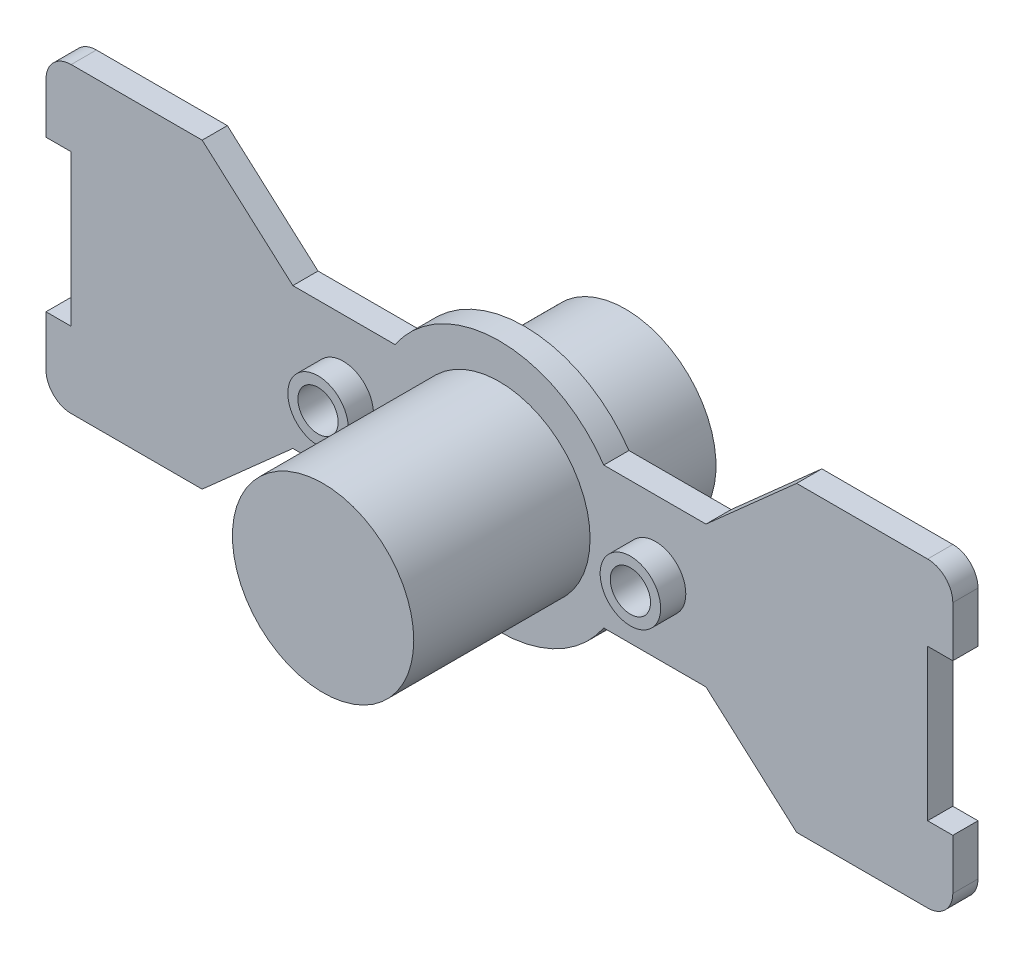
SolidWorks part; units mm, degrees
ref_plane "前视基准面" through (0, 0, 0) normal (0, 0, 1) x (1, 0, 0)
ref_plane "上视基准面" through (0, 0, 0) normal (0, 1, 0) x (1, 0, 0)
ref_plane "右视基准面" through (0, 0, 0) normal (1, 0, 0) x (0, 0, -1)
sketch "草图1" plane through (0, 0, 0) normal (0, 0, 1) x (1, 0, 0)
  line L0 (-20.7123, 14) -> (-41, 14)
  line L1 (-41, 14) -> (-59, 30)
  line L2 (-59, 30) -> (-90, 30)
  line L3 (-90, 15) -> (-90, 30)
  line L4 (-90, 15) -> (-85, 15)
  line L5 (-85, 15) -> (-85, -15)
  line L6 (-85, -15) -> (-90, -15)
  line L7 (-90, -15) -> (-90, -30)
  line L8 (-90, -30) -> (-59, -30)
  line L9 (-59, -30) -> (-41, -14)
  line L10 (-41, -14) -> (-20.7123, -14)
  line L12 (0, 25) -> (0, 38.7595) construction
  line L13 (41, -14) -> (20.7123, -14)
  line L14 (59, -30) -> (41, -14)
  line L15 (90, -30) -> (59, -30)
  line L16 (90, -15) -> (90, -30)
  line L17 (85, -15) -> (90, -15)
  line L18 (85, 15) -> (85, -15)
  line L19 (90, 15) -> (85, 15)
  line L20 (90, 15) -> (90, 30)
  line L21 (59, 30) -> (90, 30)
  line L22 (20.7123, 14) -> (41, 14)
  line L23 (41, 14) -> (59, 30)
  line L24 (25, 0) -> (85, 0) construction
  arc A0 (20.7123, 14) -> (-20.7123, 14) centre (0, 0) ccw
  arc A1 (-20.7123, -14) -> (20.7123, -14) centre (0, 0) ccw
  point P17 (0, 0)
  dimension "D1" = 50
  dimension "D2" = 41
  dimension "D3" = 59
  dimension "D4" = 85
  dimension "D5" = 90
  dimension "D6" = 30
  dimension "D7" = 60
  dimension "D8" = 28
extrude "凸台-拉伸1" add sketch "草图1" along normal blind 5
sketch "草图2" plane through (0, 0, 5) normal (0, 0, 1) x (1, 0, 0)
  circle A0 centre (0, 0) radius 18
extrude "凸台-拉伸2" add sketch "草图2" along normal blind 35
sketch "草图3" plane through (0, 0, 0) normal (0, 0, -1) x (-1, 0, 0)
  circle A0 centre (0, 0) radius 18
extrude "凸台-拉伸3" add sketch "草图3" along normal blind 20
sketch "草图4" plane through (0, 0, -20) normal (0, 0, -1) x (-1, 0, 0)
  circle A0 centre (0, 0) radius 15
  dimension "D1" = 30
extrude "切除-拉伸1" cut sketch "草图4" against normal blind 55
sketch "草图5" plane through (0, 0, 5) normal (0, 0, 1) x (1, 0, 0)
  circle A0 centre (-31, 0) radius 6
  circle A1 centre (31, 0) radius 6
  circle A2 centre (-31, 0) radius 4
  circle A3 centre (31, 0) radius 4
  dimension "D1" = 12
  dimension "D2" = 8
  dimension "D3" = 31
  dimension "D4" = 62
extrude "凸台-拉伸4" add sketch "草图5" along normal blind 5
sketch "草图6" plane through (0, 0, 5) normal (0, 0, 1) x (1, 0, 0)
  circle A0 centre (31, 0) radius 4 construction
  circle A1 centre (-31, 0) radius 4 construction
  circle A2 centre (31, 0) radius 4
  circle A3 centre (-31, 0) radius 4
extrude "切除-拉伸2" cut sketch "草图6" against normal up to next
fillet "圆角1" radius 5 4 edges at (90, -30, 2.5) (90, 30, 2.5) (-90, -30, 2.5) (-90, 30, 2.5)
